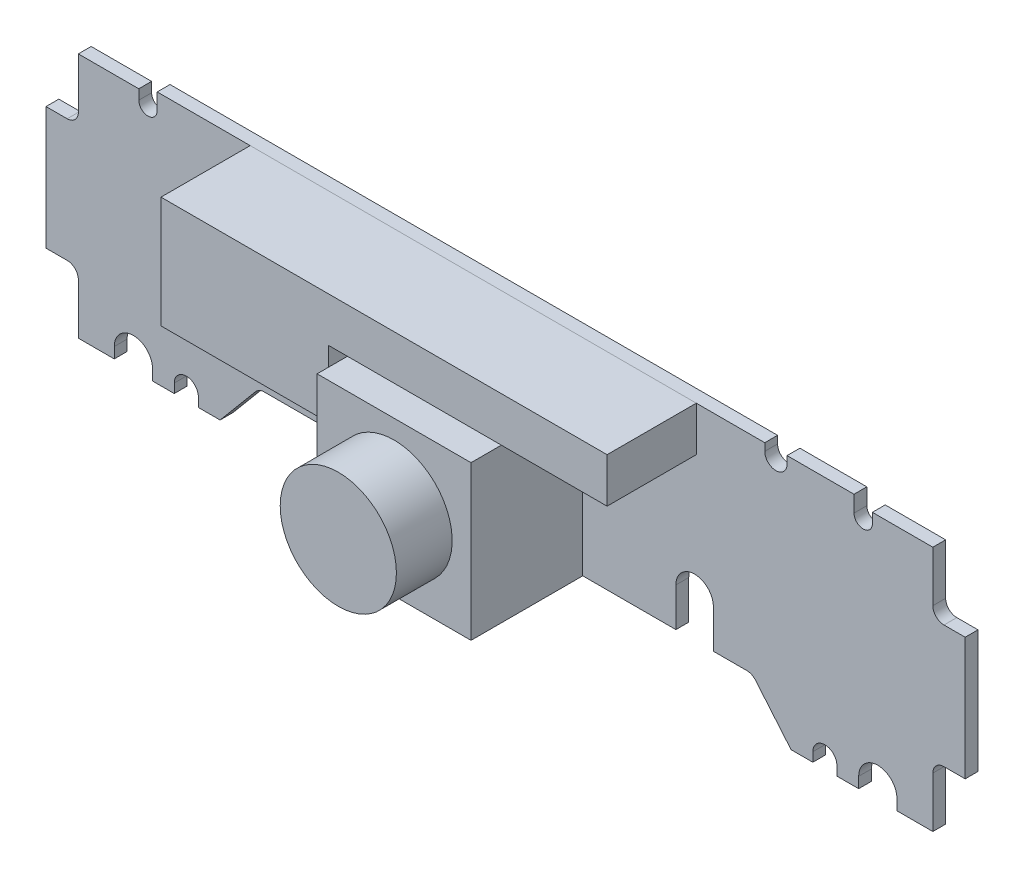
SolidWorks part; units mm, degrees
ref_plane "Front Plane" through (0, 0, 0) normal (0, 0, 1) x (1, 0, 0)
ref_plane "Top Plane" through (0, 0, 0) normal (0, 1, 0) x (1, 0, 0)
ref_plane "Right Plane" through (0, 0, 0) normal (1, 0, 0) x (0, 0, -1)
sketch "Sketch1" plane through (0, 0, 0) normal (0, 0, 1) x (1, 0, 0)
  line L0 (38.3101, -11.04) -> (38.3101, -5.5)
  line L1 (38.3101, -5.5) -> (41.2101, -5.5)
  line L2 (41.2101, -5.5) -> (41.2101, 5.5)
  line L3 (41.2101, 5.5) -> (38.3101, 5.5)
  line L4 (38.3101, 5.5) -> (38.3101, 11.04)
  line L5 (38.3101, 11.04) -> (32.8901, 11.04)
  line L6 (32.8901, 11.04) -> (32.8901, 10.155)
  line L7 (-41.2101, 5.5) -> (41.2101, -5.5) construction
  line L8 (31.2401, 10.155) -> (31.2401, 11.62)
  line L9 (31.2401, 11.62) -> (25.2401, 11.62)
  line L10 (25.2401, 11.62) -> (25.2401, 10.95)
  line L11 (41.2101, 5.5) -> (-41.2101, -5.5) construction
  line L12 (23.2401, 10.95) -> (23.2401, 11.62)
  line L13 (23.2401, 11.62) -> (-31.2401, 11.62)
  line L14 (-31.2401, 11.62) -> (-31.2401, 10.155)
  line L15 (-32.8901, 10.155) -> (-31.2401, 10.155) construction
  line L16 (-32.8901, 10.155) -> (-32.8901, 11.04)
  line L17 (-32.8901, 11.04) -> (-38.3101, 11.04)
  line L18 (-38.3101, 11.04) -> (-38.3101, 5.5)
  line L19 (-38.3101, 5.5) -> (-41.2101, 5.5)
  line L20 (-41.2101, 5.5) -> (-41.2101, -5.5)
  line L21 (-41.2101, -5.5) -> (-38.3101, -5.5)
  line L22 (-38.3101, -5.5) -> (-38.3101, -11.04)
  line L23 (-38.3101, -11.04) -> (-35.0901, -11.04)
  line L24 (-35.0901, -11.04) -> (-35.0901, -10.075)
  line L26 (-31.6601, -10.075) -> (-31.6601, -11.04)
  line L27 (-31.6601, -11.04) -> (-29.7101, -11.04)
  line L28 (-29.7101, -11.04) -> (-29.7101, -10.22)
  line L30 (-27.5501, -10.22) -> (-27.5501, -11.04)
  line L31 (-27.5501, -11.04) -> (-25.6001, -11.04)
  line L32 (-25.6001, -11.04) -> (-22.1095, -6.88)
  line L33 (-22.1095, -6.88) -> (15.2701, -6.88)
  line L34 (15.2701, -6.88) -> (15.2701, -3.41)
  line L36 (18.6301, -3.41) -> (18.6301, -6.88)
  line L37 (18.6301, -6.88) -> (22.1095, -6.88)
  line L38 (22.1095, -6.88) -> (25.6001, -11.04)
  line L39 (25.6001, -11.04) -> (27.5501, -11.04)
  line L40 (27.5501, -11.04) -> (27.5501, -10.22)
  line L42 (29.7101, -10.22) -> (29.7101, -11.04)
  line L43 (29.7101, -11.04) -> (31.6601, -11.04)
  line L44 (31.6601, -11.04) -> (31.6601, -10.075)
  line L46 (35.0901, -10.075) -> (35.0901, -11.04)
  line L47 (35.0901, -11.04) -> (38.3101, -11.04)
  arc A0 (31.2401, 10.155) -> (32.8901, 10.155) centre (32.0651, 10.155) ccw
  arc A1 (23.2401, 10.95) -> (25.2401, 10.95) centre (24.2401, 10.95) ccw
  arc A2 (-32.8901, 10.155) -> (-31.2401, 10.155) centre (-32.0651, 10.155) ccw
  arc A3 (-31.6601, -10.075) -> (-35.0901, -10.075) centre (-33.3751, -10.075) ccw
  arc A4 (18.6301, -3.41) -> (15.2701, -3.41) centre (16.9501, -3.41) ccw
  arc A5 (29.7101, -10.22) -> (27.5501, -10.22) centre (28.6301, -10.22) ccw
  arc A6 (35.0901, -10.075) -> (31.6601, -10.075) centre (33.3751, -10.075) ccw
  arc A7 (-27.5501, -10.22) -> (-29.7101, -10.22) centre (-28.6301, -10.22) ccw
  point P50 (0, 0)
  point P52 (-32.0651, 10.155)
  point P54 (-28.6301, -9.14)
  point P56 (24.2401, 9.95)
  point P58 (32.0651, 9.33)
  point P60 (16.9501, -1.73)
  dimension "D7" = 0.965
  dimension "D12" = 2.16
  dimension "D17" = 0.825
  dimension "D1" = 11
  dimension "D2" = 6
  dimension "D3" = 0.58
  dimension "D4" = 18.5
  dimension "D5" = 3.22
  dimension "D6" = 3.43
  dimension "D8" = 5.54
  dimension "D9" = 82.4203
  dimension "D10" = 3.43
  dimension "D11" = 1.95
  dimension "D13" = 2.16
  dimension "D14" = 1.9
  dimension "D15" = 2.9
  dimension "D16" = 3.36
  dimension "D18" = 5.42
  dimension "D19" = 2.29
  dimension "D20" = 130
  dimension "D21" = 2
  dimension "D22" = 1.67
  dimension "D23" = 5.15
  dimension "D24" = 19.68
  dimension "D25" = 130
extrude "Boss-Extrude1" add sketch "Sketch1" along normal blind 1.15
sketch "Sketch2" plane through (0, 0, 1.15) normal (0, 0, 1) x (1, 0, 0)
  circle A0 centre (0, 0) radius 5.21
  dimension "D1" = 10.42
extrude "Boss-Extrude2" add sketch "Sketch2" along normal blind 15
sketch "Sketch3" plane through (0, 0, 1.15) normal (0, 0, 1) x (1, 0, 0)
  line L1 (6.9, 6.9) -> (-6.9, 6.9)
  line L2 (6.9, 6.9) -> (6.9, -6.9)
  line L3 (6.9, -6.9) -> (-6.9, -6.9)
  line L4 (-6.9, 6.9) -> (-6.9, -6.9)
  line L5 (6.9, 6.9) -> (-6.9, -6.9) construction
  line L6 (6.9, -6.9) -> (-6.9, 6.9) construction
  point P0 (0, 0)
  dimension "D1" = 13.8
extrude "Boss-Extrude3" add sketch "Sketch3" along normal blind 10
fillet "Fillet1" radius 1 6 edges at (22.1095, -6.88, 0.575) (-22.1095, -6.88, 0.575) (-38.3101, -5.5, 0.575) (-38.3101, 5.5, 0.575) (38.3101, 5.5, 0.575) (38.3101, -5.5, 0.575)
sketch "Sketch4" plane through (0, 0, 1.15) normal (0, 0, 1) x (1, 0, 0)
  line L0 (-7.9, 7.62) -> (-7.9, 1.62)
  line L1 (-7.9, 1.62) -> (-22.9, 1.62)
  line L2 (-22.9, 1.62) -> (-22.9, 11.62)
  line L3 (-22.9, 11.62) -> (17.1, 11.62)
  line L4 (17.1, 11.62) -> (17.1, 7.62)
  line L5 (17.1, 7.62) -> (-7.9, 7.62)
  line L6 (23.2401, 11.62) -> (-31.2401, 11.62) construction
  line L7 (-6.9, 6.9) -> (-6.9, -6.88) construction
  dimension "D1" = 16
  dimension "D2" = 40
  dimension "D3" = 10
  dimension "D4" = 4
  dimension "D5" = 25
extrude "Boss-Extrude4" add sketch "Sketch4" along normal blind 8 separate body
